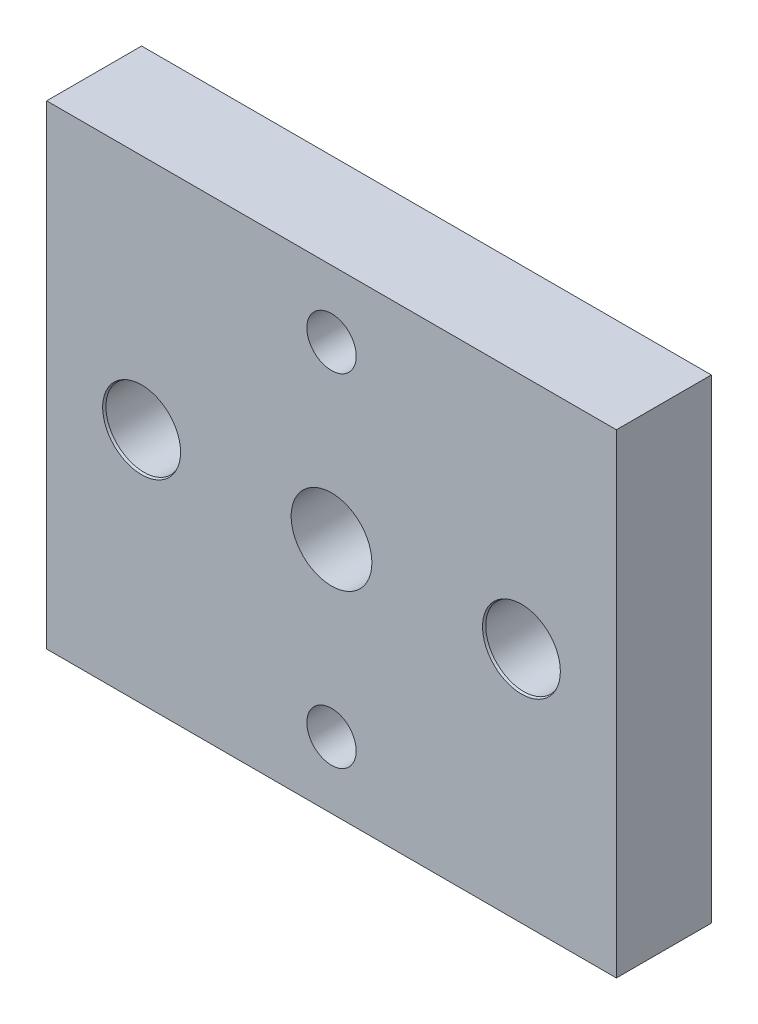
SolidWorks part; units mm, degrees
ref_plane "前视基准面" through (0, 0, 0) normal (0, 0, 1) x (1, 0, 0)
ref_plane "上视基准面" through (0, 0, 0) normal (0, 1, 0) x (1, 0, 0)
ref_plane "右视基准面" through (0, 0, 0) normal (1, 0, 0) x (0, 0, -1)
other "Configuration Table"
sketch "草图1" plane through (0, 0, 0) normal (0, 0, 1) x (1, 0, 0)
  line L1 (-30, -25) -> (30, -25)
  line L2 (-30, -25) -> (-30, 25)
  line L3 (-30, 25) -> (30, 25)
  line L4 (30, -25) -> (30, 25)
  line L5 (-30, -25) -> (30, 25) construction
  line L6 (-30, 25) -> (30, -25) construction
  point P0 (0, 0)
  dimension "D1" = 50
  dimension "D2" = 60
extrude "凸台-拉伸1" add sketch "草图1" along normal blind 10
hole_wizard "孔1" positions "草图2" profile "草图3" legacy
sketch "草图2" plane through (0, 0, 10) normal (0, 0, 1) x (1, 0, 0)
  point P0 (0, 0)
sketch "草图3" plane through (0, 0, 10) normal (1, 0, 0) x (0, -1, 0)
  line L0 (0, 0) -> (0, 20)
  line L1 (0, 20) -> (4.25, 20)
  line L2 (4.25, 20) -> (4.25, 0)
  line L3 (4.25, 0) -> (0, 0)
  line L4 (0, 110) -> (0, -10) construction
  dimension "直径" = 8.5
  dimension "深度" = 20
hole_wizard "孔2" positions "草图4" profile "草图5" legacy end condition through all
sketch "草图4" plane through (0, 0, 10) normal (0, 0, 1) x (1, 0, 0)
  point P0 (20, 0)
  point P2 (-20, 0)
  dimension "D1" = 20
  dimension "D2" = 20
sketch "草图5" plane through (20, 0, 10) normal (1, 0, 0) x (0, -1, 0)
  line L0 (0, 0) -> (0, 10)
  line L1 (0, 10) -> (4, 10)
  line L2 (4, 10) -> (4, 0.2414)
  line L3 (4, 0.2414) -> (4.1, 0)
  line L4 (4.1, 0) -> (0, 0)
  line L5 (0, -6.4453) -> (0, 115.525) construction
  line L6 (-4, 0.2414) -> (-4.1, 0) construction
  dimension "直径" = 8
  dimension "深度" = 10
  dimension "锥坑角度" = 45
  dimension "锥坑直径" = 8.2
hole_wizard "孔3" positions "草图6" profile "草图7" legacy end condition through all
sketch "草图6" plane through (0, 0, 0) normal (0, 0, -1) x (-1, 0, 0)
  point P0 (0, 18)
  point P2 (0, -18)
  dimension "D1" = 18
  dimension "D2" = 18
sketch "草图7" plane through (0, 18, 0) normal (1, 0, 0) x (0, 1, 0)
  line L0 (0, 0) -> (0, 10)
  line L1 (0, 10) -> (2.6, 10)
  line L2 (2.6, 10) -> (2.6, 0)
  line L3 (2.6, 0) -> (0, 0)
  line L4 (0, 110) -> (0, -10) construction
  dimension "直径" = 5.2
  dimension "深度" = 10
